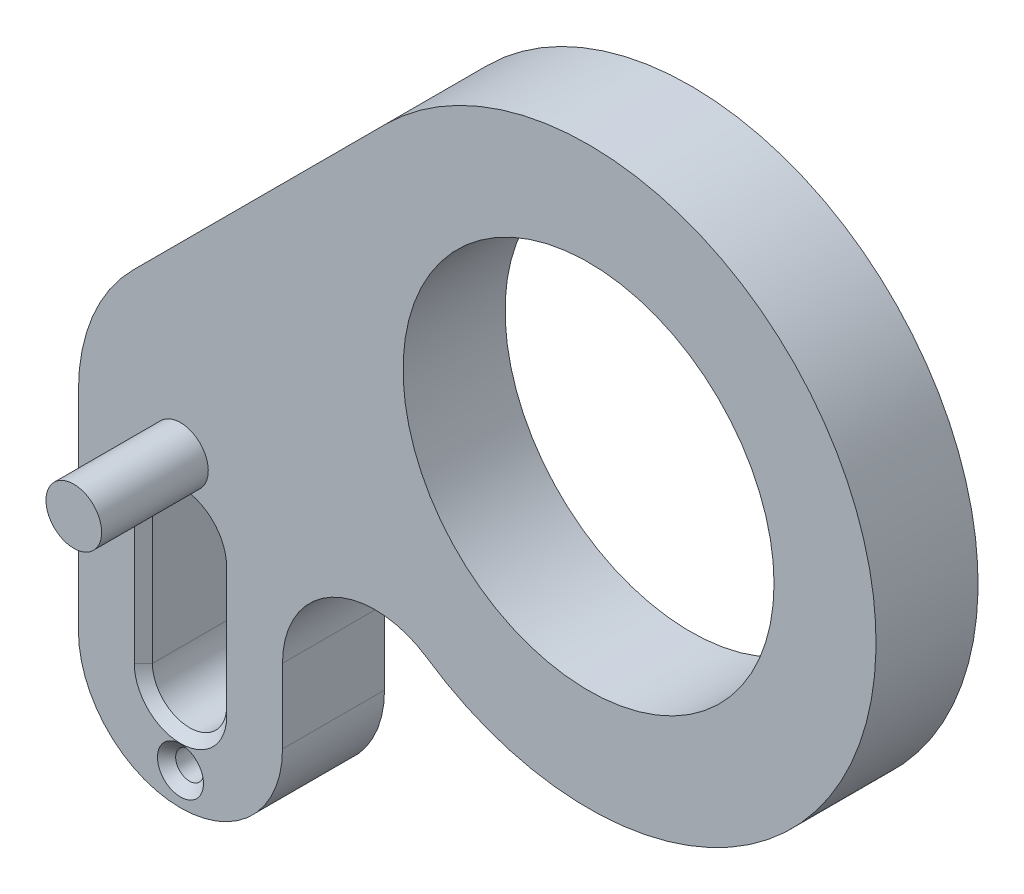
SolidWorks part; units mm, degrees
ref_plane "Plan de face" through (0, 0, 0) normal (0, 0, 1) x (1, 0, 0)
ref_plane "Plan de dessus" through (0, 0, 0) normal (0, 1, 0) x (1, 0, 0)
ref_plane "Plan de droite" through (0, 0, 0) normal (1, 0, 0) x (0, 0, -1)
sketch "Esquisse1" plane through (0, 0, 0) normal (0, 0, 1) x (1, 0, 0)
  line L0 (5.5, -3.5) -> (5.5, 0.5)
  line L1 (-5.5, -3.5) -> (-5.5, 7.7487)
  line L2 (-2.5711, 14.8198) -> (11.0398, 28.4307)
  line L3 (0, 3.5) -> (0, -3.5) construction
  line L4 (2, 3.5) -> (2, -3.5)
  line L5 (-2, 3.5) -> (-2, -3.5)
  circle A0 centre (22, 17.4706) radius 10
  arc A1 (11.0398, 28.4307) -> (13.3049, 4.6392) centre (22, 17.4706) cw
  arc A2 (13.3049, 4.6392) -> (5.5, 0.5) centre (10.5, 0.5) ccw
  arc A3 (-5.5, -3.5) -> (5.5, -3.5) centre (0, -3.5) ccw
  arc A4 (-2.5711, 14.8198) -> (-5.5, 7.7487) centre (4.5, 7.7487) ccw
  arc A5 (2, 3.5) -> (-2, 3.5) centre (0, 3.5) ccw
  arc A6 (-2, -3.5) -> (2, -3.5) centre (0, -3.5) ccw
  circle A7 centre (0, -7.25) radius 0.75
  point P0 (0, 0)
  point P3 (0, 0)
  point P22 (0, 5.5)
  point P23 (0, -5.5)
  point P24 (0, -8)
  point P25 (0, -6.5)
  point P26 (0, -9)
  point P29 (10.5, 5.5)
  dimension "D1" = 10
  dimension "D4" = 20
  dimension "D5" = 5.5
  dimension "D7" = 1.5
  dimension "D10" = 5
  dimension "D2" = 11
  dimension "D3" = 11
  dimension "D6" = 1
  dimension "D8" = 1
  dimension "D9" = 135
  dimension "D11" = 22
extrude "Boss.-Extru.1" add sketch "Esquisse1" along normal mid plane 5.5
chamfer "Chanfrein1" distance 0.49 angle 45 5 edges at (0.75, -7.25, 2.75) (0, -5.5, 2.75) (-2, 0, 2.75) (2, 0, 2.75) (0, 5.5, 2.75)
chamfer "Chanfrein2" distance 0.49 angle 45 5 edges at (0.75, -7.25, -2.75) (0, 5.5, -2.75) (2, 0, -2.75) (-2, 0, -2.75) (0, -5.5, -2.75)
sketch "Esquisse2" plane through (0, 0, 0) normal (0, 0, 1) x (1, 0, 0)
  line L0 (0, -6.01) -> (0, 5.99) construction
  circle A0 centre (0, 7.49) radius 1.5
  circle A1 centre (0, -7.25) radius 1.24 construction
  arc A2 (2.49, 3.5) -> (-2.49, 3.5) centre (0, 3.5) ccw construction
  dimension "D1" = 3
extrude "Boss.-Extru.2" add sketch "Esquisse2" along normal mid plane 17
